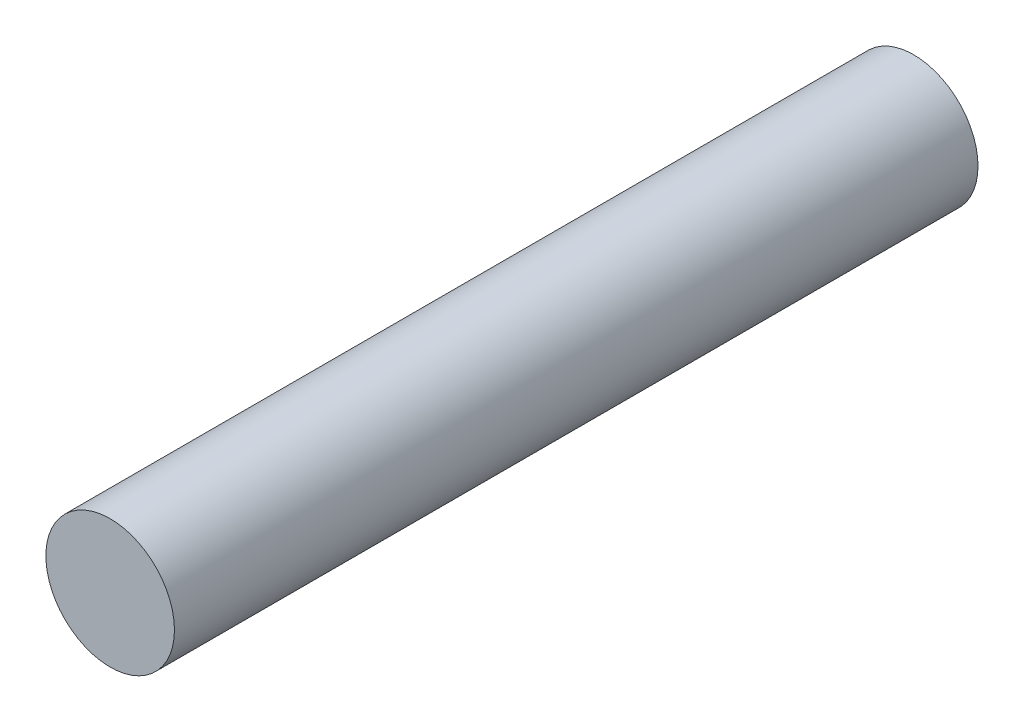
SolidWorks part; units mm, degrees
ref_plane "Front Plane" through (0, 0, 0) normal (0, 0, 1) x (1, 0, 0)
ref_plane "Top Plane" through (0, 0, 0) normal (0, 1, 0) x (1, 0, 0)
ref_plane "Right Plane" through (0, 0, 0) normal (1, 0, 0) x (0, 0, -1)
sketch "Sketch1" plane through (0, 0, 0) normal (0, 0, 1) x (1, 0, 0)
  circle A0 centre (0, 0) radius 14
extrude "Boss-Extrude1" add sketch "Sketch1" along normal blind 175
